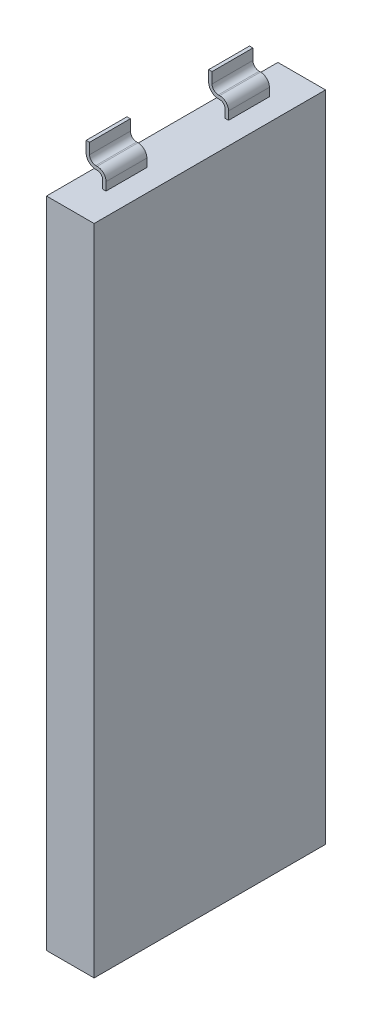
SolidWorks part; units mm, degrees
ref_plane "前视" through (0, 0, 0) normal (0, 0, 1) x (1, 0, 0)
ref_plane "上视" through (0, 0, 0) normal (0, 1, 0) x (1, 0, 0)
ref_plane "右视" through (0, 0, 0) normal (1, 0, 0) x (0, 0, -1)
sketch "草图1" plane through (0, 0, 0) normal (1, 0, 0) x (0, 0, -1)
  line L1 (-17, 48) -> (17, 48)
  line L2 (-17, 48) -> (-17, -48)
  line L3 (-17, -48) -> (17, -48)
  line L4 (17, 48) -> (17, -48)
  dimension "D1" = 96
  dimension "D2" = 34
  dimension "D3" = 17
  dimension "D4" = 48
extrude "凸台-拉伸1" add sketch "草图1" along normal blind 7
ref_plane "基准面1" through (0, 0, 9) normal (0, 0, 1) x (1, 0, 0)
sketch "草图2" plane through (0, 0, 9) normal (0, 0, 1) x (1, 0, 0)
  line L0 (3.25, 48) -> (3.25, 49.2)
  line L1 (7, 48) -> (0, 48) construction
  line L2 (1.33, 53) -> (1.33, 51.42)
  line L3 (0.83, 53) -> (0.83, 51.42)
  line L4 (2.25, 50) -> (2.45, 50)
  line L5 (0, 48) -> (0, -48) construction
  line L6 (2.25, 50.5) -> (2.45, 50.5)
  line L7 (3.75, 48) -> (3.75, 49.2)
  line L8 (0.83, 53) -> (1.33, 53)
  line L9 (3.25, 48) -> (3.75, 48)
  arc A0 (0.83, 51.42) -> (2.25, 50) centre (2.25, 51.42) ccw
  arc A1 (3.25, 49.2) -> (2.45, 50) centre (2.45, 49.2) ccw
  arc A2 (1.33, 51.42) -> (2.25, 50.5) centre (2.25, 51.42) ccw
  arc A3 (3.75, 49.2) -> (2.45, 50.5) centre (2.45, 49.2) ccw
  point P10 (0.83, 50)
  point P13 (3.25, 50)
  dimension "D5" = 1.42
  dimension "D6" = 0.8
  dimension "D1" = 3
  dimension "D2" = 0.83
  dimension "D3" = 2
  dimension "D4" = 3.25
  dimension "D7" = 0.5
extrude "凸台-拉伸2" add sketch "草图2" along normal mid plane 6
mirror "镜向1" about plane through (0, 0, 0) normal (0, 0, 1) of "凸台-拉伸2"
